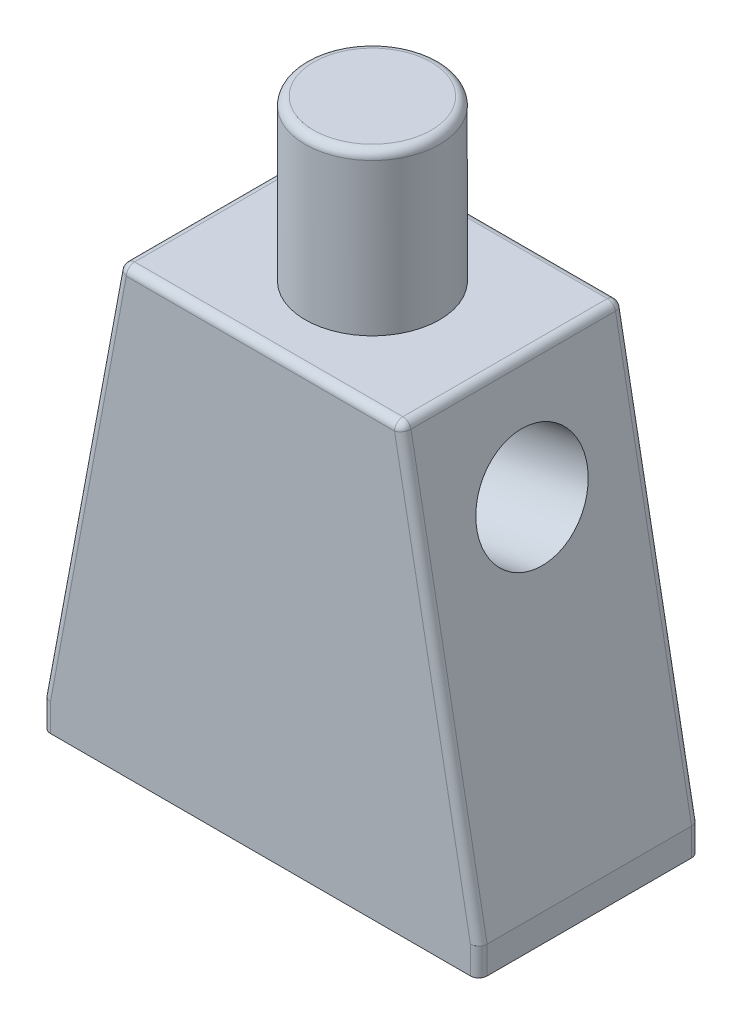
SolidWorks part; units mm, degrees
ref_plane "Front Plane" through (0, 0, 0) normal (0, 0, 1) x (1, 0, 0)
ref_plane "Top Plane" through (0, 0, 0) normal (0, 1, 0) x (1, 0, 0)
ref_plane "Right Plane" through (0, 0, 0) normal (1, 0, 0) x (0, 0, -1)
sketch "Sketch1" plane through (0, 0, 0) normal (0, 0, 1) x (1, 0, 0)
  line L0 (129.54, 113.9624) -> (-129.54, 113.9624)
  line L1 (-129.54, 113.9624) -> (-200.66, -267.0376)
  line L2 (-200.66, -267.0376) -> (200.66, -267.0376)
  line L3 (200.66, -267.0376) -> (129.54, 113.9624)
  dimension "D1" = 259.08
  dimension "D2" = 401.32
  dimension "D3" = 381
  dimension "D4" = 381
  dimension "D5" = 129.54
  dimension "D6" = 200.66
extrude "Boss-Extrude1" add sketch "Sketch1" along normal blind 203.2
fillet "Fillet1" radius 7.62 8 edges at (165.1, -76.5376, 0) (165.1, -76.5376, 203.2) (-165.1, -76.5376, 0) (-165.1, -76.5376, 203.2) (129.54, 113.9624, 101.6) (0, 113.9624, 0) (-129.54, 113.9624, 101.6) (0, 113.9624, 203.2)
sketch "Sketch2" plane through (0, 113.9624, 0) normal (0, 1, 0) x (1, 0, 0)
  line L0 (-123.2108, 0) -> (123.2108, 0) construction
  line L1 (123.2108, -195.58) -> (123.2108, -7.62) construction
  circle A0 centre (1.2908, -101.5918) radius 61.722
  point P4 (0, 0)
  dimension "D3" = 123.444
  dimension "D1" = 101.6
  dimension "D2" = 121.92
extrude "Boss-Extrude2" add sketch "Sketch2" along normal blind 147.1422
fillet "Fillet2" radius 7.62 1 edges at (-60.4312, 261.1046, 101.5918)
sketch "Sketch4" plane through (0, -267.0376, 0) normal (0, -1, 0) x (-1, 0, 0)
  line L0 (200.66, -195.58) -> (200.66, -7.62) construction
  line L1 (-200.66, -195.58) -> (-200.66, -7.62) construction
  circle A0 centre (100.33, -101.6) radius 61.722
  circle A1 centre (-100.33, -101.6) radius 61.722
  point P5 (0, 0)
  point P6 (0, 0)
  dimension "D1" = 123.444
  dimension "D2" = 100.33
  dimension "D3" = 101.6
  dimension "D5" = 200.66
  dimension "D6" = 100.33
  dimension "D4" = 2
extrude "Cut-Extrude2" cut sketch "Sketch4" against normal blind 121.7422
sketch "Sketch5" plane through (-145.7349, 27.2039, 0) normal (-0.983, 0.1835, 0) x (0, 0, 1)
  line L0 (195.58, 81.9279) -> (7.62, 81.9279) construction
  line L1 (195.58, -299.3239) -> (195.58, 81.9279) construction
  circle A0 centre (101.6, -12.0521) radius 50.8
  dimension "D2" = 101.6
  dimension "D1" = 93.98
  dimension "D3" = 93.98
sketch "Sketch6" plane through (145.7349, 27.2039, 0) normal (0.983, 0.1835, 0) x (0, 0, -1)
  line L0 (-7.62, 81.9279) -> (-195.58, 81.9279) construction
  line L1 (-7.62, -299.3239) -> (-7.62, 81.9279) construction
  circle A0 centre (-101.6, -12.0521) radius 50.8
  dimension "D2" = 101.6
  dimension "D1" = 93.98
  dimension "D3" = 93.98
extrude "Cut-Extrude3" cut sketch "Sketch6" against normal blind 101.6
extrude "Cut-Extrude4" cut sketch "Sketch5" against normal blind 101.6 contours A0
sketch "Sketch7" plane through (0, -267.0376, 0) normal (0, -1, 0) x (1, 0, 0)
  line L0 (-192.9084, 0) -> (192.9084, 0) construction
  line L1 (-200.66, 203.2) -> (200.66, 203.2)
  line L2 (-200.66, 203.2) -> (-200.66, 0)
  line L3 (-200.66, 0) -> (200.66, 0)
  line L4 (200.66, 203.2) -> (200.66, 0)
  circle A0 centre (-100.33, 101.6) radius 61.722
  circle A1 centre (100.33, 101.6) radius 61.722
  dimension "D1" = 203.2
  dimension "D2" = 401.32
  dimension "D3" = 200.66
  dimension "D4" = 203.2
extrude "Boss-Extrude3" add sketch "Sketch7" along normal blind 25.4
fillet "Fillet3" radius 7.62 4 edges at (-200.66, -279.7376, 0) (200.66, -279.7376, 203.2) (200.66, -279.7376, 0) (-200.66, -279.7376, 203.2)
